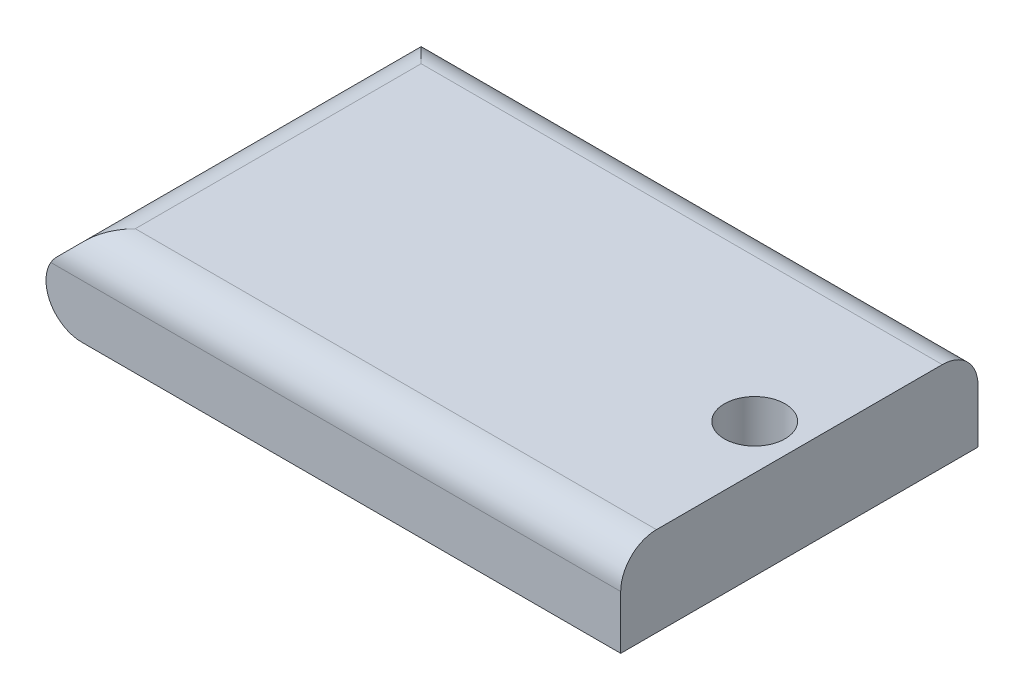
SolidWorks part; units mm, degrees
ref_plane "Front Plane" through (0, 0, 0) normal (0, 0, 1) x (1, 0, 0)
ref_plane "Top Plane" through (0, 0, 0) normal (0, 1, 0) x (1, 0, 0)
ref_plane "Right Plane" through (0, 0, 0) normal (1, 0, 0) x (0, 0, -1)
sketch "ｽｹｯﾁ1" plane through (0, 0, 0) normal (0, 0, 1) x (1, 0, 0)
  line L0 (0, 0) -> (-35, 0)
  line L1 (-35, 0) -> (-30, 5)
  line L2 (-30, 5) -> (0, 5)
  line L3 (0, 5) -> (0, 0)
  dimension "D1" = 35
  dimension "D2" = 30
  dimension "D3" = 5
extrude "ﾎﾞｽ - 押し出し1" add sketch "ｽｹｯﾁ1" along normal blind 20
sketch "ｽｹｯﾁ2" plane through (0, 5, 0) normal (0, 1, 0) x (1, 0, 0)
  line L0 (0, -20) -> (-30, -20) construction
  line L1 (0, 0) -> (-5, 0) construction
  line L2 (0, 0) -> (0, -20) construction
  line L3 (0, -20) -> (-5, -20) construction
  line L4 (-5, 0) -> (-5, -20) construction
  line L5 (-2.5, -20) -> (-2.5, 0) construction
  line L6 (0, -10) -> (-5, -10) construction
  circle A0 centre (-2.5, -10) radius 1.7
  point P172 (-2.5, -10)
  dimension "D2" = 3.4
  dimension "D1" = 5
extrude "ｶｯﾄ - 押し出し1" cut sketch "ｽｹｯﾁ2" against normal through all
fillet "ﾌｨﾚｯﾄ1" radius 2 3 edges at (-15, 5, 0) (-15, 5, 20) (-30, 5, 10)
fillet "ﾌｨﾚｯﾄ2" radius 2 1 edges at (-35, 0, 10)
